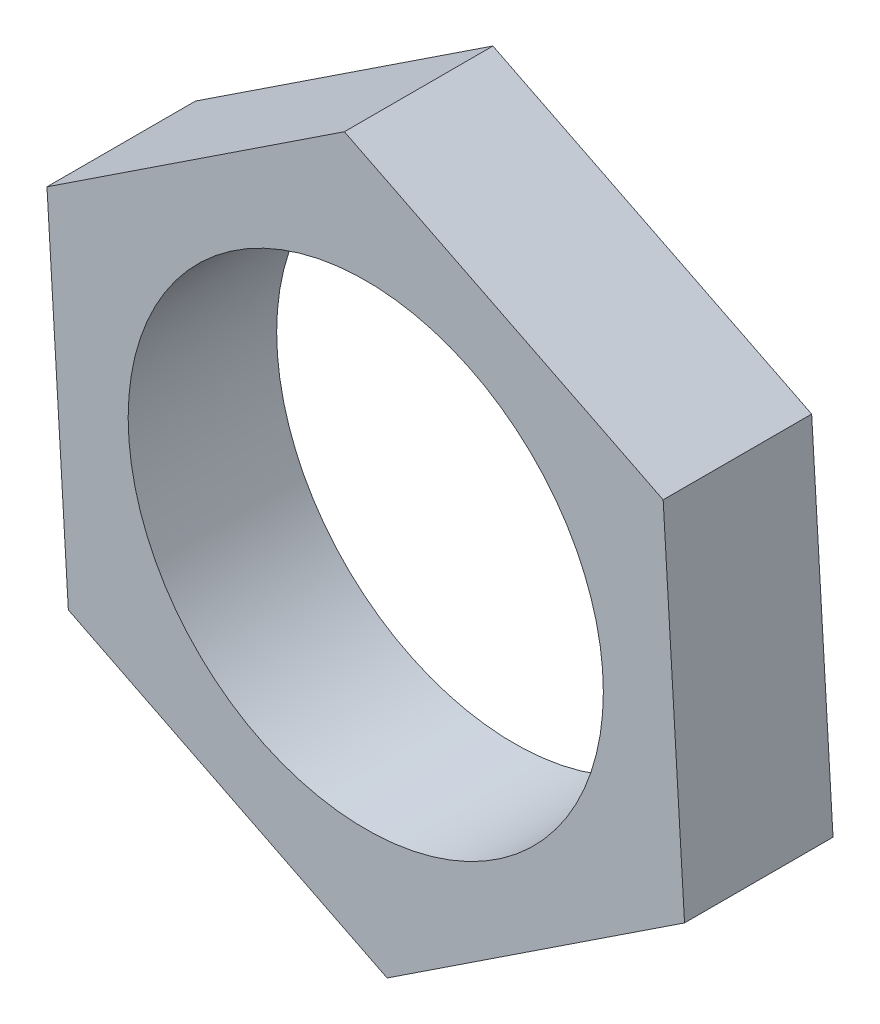
SolidWorks part; units mm, degrees
ref_plane "Front Plane" through (0, 0, 0) normal (0, 0, 1) x (1, 0, 0)
ref_plane "Top Plane" through (0, 0, 0) normal (0, 1, 0) x (1, 0, 0)
ref_plane "Right Plane" through (0, 0, 0) normal (1, 0, 0) x (0, 0, -1)
sketch "Sketch1" plane through (0, 0, 0) normal (0, 0, 1) x (1, 0, 0)
  line L1 (-0.7196, 11.9784) -> (-10.7334, 5.3661)
  line L2 (-10.7334, 5.3661) -> (-10.0138, -6.6124)
  line L3 (-10.0138, -6.6124) -> (0.7196, -11.9784)
  line L4 (0.7196, -11.9784) -> (10.7334, -5.3661)
  line L5 (10.7334, -5.3661) -> (10.0138, 6.6124)
  line L6 (10.0138, 6.6124) -> (-0.7196, 11.9784)
  circle A0 centre (0, 0) radius 10.3923 construction
  circle A1 centre (0, 0) radius 8
  dimension "D2" = 16
  dimension "D1" = 12
extrude "Boss-Extrude1" add sketch "Sketch1" along normal blind 5
